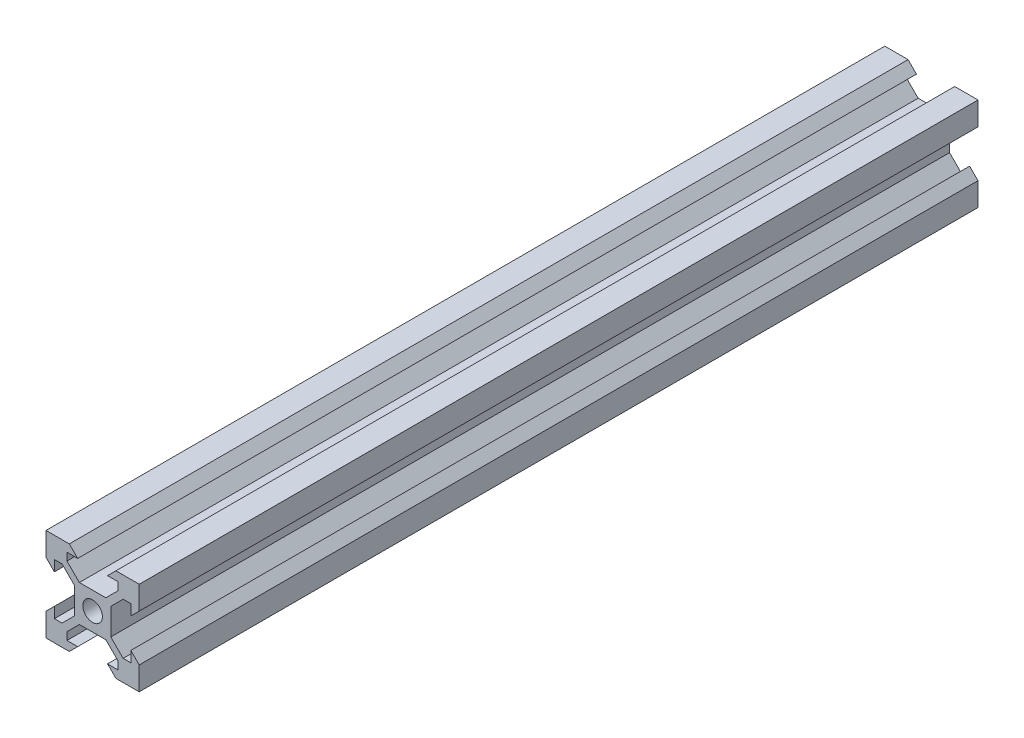
SolidWorks part; units mm, degrees
ref_plane "Front Plane" through (0, 0, 0) normal (0, 0, 1) x (1, 0, 0)
ref_plane "Top Plane" through (0, 0, 0) normal (0, 1, 0) x (1, 0, 0)
ref_plane "Right Plane" through (0, 0, 0) normal (1, 0, 0) x (0, 0, -1)
sketch "Sketch1" plane through (0, 0, 0) normal (0, 0, 1) x (1, 0, 0)
  line L0 (-10, 10) -> (-10, 5)
  line L1 (-10, 5) -> (-8.2, 3.2)
  line L2 (-8.2, 3.2) -> (-8.2, 5.4993)
  line L3 (-8.2, 5.4993) -> (-6.56, 5.4993)
  line L4 (-6.56, 5.4993) -> (-3.9007, 2.84)
  line L5 (-3.9007, 2.84) -> (-3.9007, -2.84)
  line L6 (-3.9007, -2.84) -> (-6.56, -5.4993)
  line L7 (-6.56, -5.4993) -> (-8.2, -5.4993)
  line L8 (-8.2, -5.4993) -> (-8.2, -3.2)
  line L9 (-8.2, -3.2) -> (-10, -5)
  line L10 (-10, -5) -> (-10, -10)
  line L11 (-10, -10) -> (-5, -10)
  line L12 (-5, -10) -> (-3.2, -8.2)
  line L13 (-3.2, -8.2) -> (-5.4993, -8.2)
  line L14 (-5.4993, -8.2) -> (-5.4993, -6.56)
  line L15 (-5.4993, -6.56) -> (-2.84, -3.9007)
  line L16 (-2.84, -3.9007) -> (2.84, -3.9007)
  line L17 (2.84, -3.9007) -> (5.4993, -6.56)
  line L18 (5.4993, -6.56) -> (5.4993, -8.2)
  line L19 (5.4993, -8.2) -> (3.2, -8.2)
  line L20 (3.2, -8.2) -> (5, -10)
  line L21 (5, -10) -> (10, -10)
  line L22 (10, -10) -> (10, -5)
  line L23 (10, -5) -> (8.2, -3.2)
  line L24 (8.2, -3.2) -> (8.2, -5.4993)
  line L25 (8.2, -5.4993) -> (6.56, -5.4993)
  line L26 (6.56, -5.4993) -> (3.9007, -2.84)
  line L27 (3.9007, -2.84) -> (3.9007, 2.84)
  line L28 (3.9007, 2.84) -> (6.56, 5.4993)
  line L29 (6.56, 5.4993) -> (8.2, 5.4993)
  line L30 (8.2, 5.4993) -> (8.2, 3.2)
  line L31 (8.2, 3.2) -> (10, 5)
  line L32 (10, 5) -> (10, 10)
  line L33 (10, 10) -> (5, 10)
  line L34 (5, 10) -> (3.2, 8.2)
  line L35 (3.2, 8.2) -> (5.4993, 8.2)
  line L36 (5.4993, 8.2) -> (5.4993, 6.56)
  line L37 (5.4993, 6.56) -> (2.84, 3.9007)
  line L38 (2.84, 3.9007) -> (-2.84, 3.9007)
  line L39 (-2.84, 3.9007) -> (-5.4993, 6.56)
  line L40 (-5.4993, 6.56) -> (-5.4993, 8.2)
  line L41 (-5.4993, 8.2) -> (-3.2, 8.2)
  line L42 (-3.2, 8.2) -> (-5, 10)
  line L43 (-5, 10) -> (-10, 10)
  circle A0 centre (0, 0) radius 2.1
extrude "Boss-Extrude1" add sketch "Sketch1" against normal blind 180
